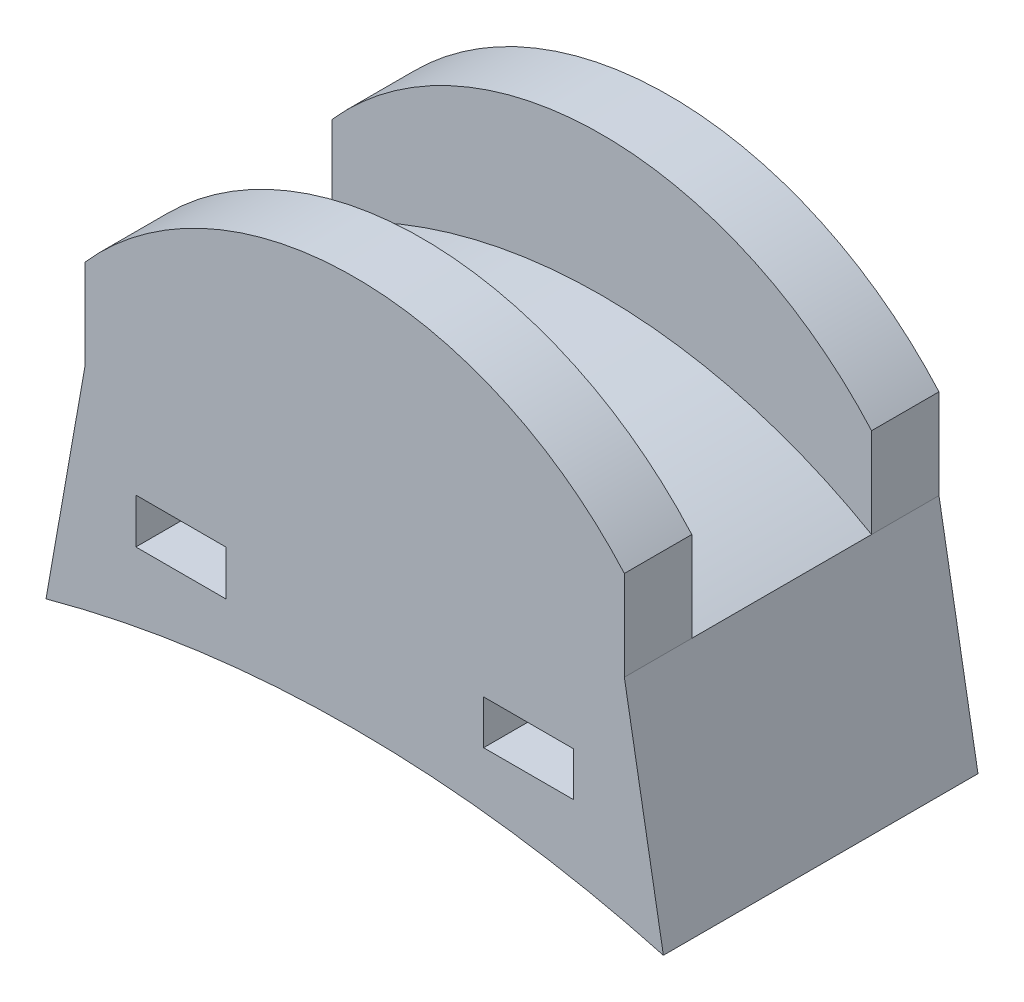
SolidWorks part; units mm, degrees
ref_plane "Front Plane" through (0, 0, 0) normal (0, 0, 1) x (1, 0, 0)
ref_plane "Top Plane" through (0, 0, 0) normal (0, 1, 0) x (1, 0, 0)
ref_plane "Right Plane" through (0, 0, 0) normal (1, 0, 0) x (0, 0, -1)
sketch "Sketch1" plane through (0, 0, 0) normal (0, 0, 1) x (1, 0, 0)
  line L1 (-76.2, 0) -> (-81.7133, -31.2676)
  line L2 (0, 0) -> (5.5133, -31.2676)
  line L3 (-81.7133, -31.2676) -> (5.5133, -31.2676)
  arc A0 (-76.2, 0) -> (0, 0) centre (-38.1, -65.9911) cw
  dimension "D2" = 31.75
  dimension "D1" = 76.2
extrude "Boss-Extrude1" add sketch "Sketch1" along normal blind 25.4
sketch "Sketch2" plane through (0, 0, 25.4) normal (0, 0, 1) x (1, 0, 0)
  line L0 (-38.1, 10.2089) -> (-38.1, 22.9089)
  line L1 (-76.2, 0) -> (-76.2, 12.7)
  line L2 (0, 0) -> (0, 12.7)
  line L3 (0, 0) -> (5.5133, -31.2676)
  line L4 (5.5133, -31.2676) -> (-81.7133, -31.2676)
  line L5 (-81.7133, -31.2676) -> (-76.2, 0)
  arc A0 (0, 0) -> (-76.2, 0) centre (-38.1, -65.9911) ccw construction
  arc A1 (0, 12.7) -> (-76.2, 12.7) centre (-38.1, -20.901) ccw
  dimension "D3" = 12.7
  dimension "D1" = 12.7
  dimension "D2" = 12.7
extrude "Boss-Extrude2" add sketch "Sketch2" along normal blind 9.525
sketch "Sketch3" plane through (0, 0, 0) normal (0, 0, -1) x (-1, 0, 0)
  line L0 (0, 0) -> (0, 12.7)
  line L1 (76.2, 0) -> (76.2, 12.7)
  line L2 (0, 0) -> (-5.5133, -31.2676)
  line L3 (-5.5133, -31.2676) -> (81.7133, -31.2676)
  line L4 (81.7133, -31.2676) -> (76.2, 0)
  arc A0 (0, 12.7) -> (76.2, 12.7) centre (38.1, -20.901) cw
extrude "Boss-Extrude3" add sketch "Sketch3" along normal blind 9.525
sketch "Sketch5" plane through (0, 0, -9.525) normal (0, 0, -1) x (-1, 0, 0)
  line L0 (-5.5133, -31.2676) -> (81.7133, -31.2676)
  arc A0 (-5.5133, -31.2676) -> (81.7133, -31.2676) centre (38.1, -190.503) cw
extrude "Cut-Extrude2" cut sketch "Sketch5" against normal through all
sketch "Sketch6" plane through (0, 0, -9.525) normal (0, 0, -1) x (-1, 0, 0)
  line L1 (7.1867, -12.3446) -> (19.8867, -12.3446)
  line L2 (7.1867, -12.3446) -> (7.1867, -18.5676)
  line L3 (7.1867, -18.5676) -> (19.8867, -18.5676)
  line L4 (19.8867, -12.3446) -> (19.8867, -18.5676)
  line L5 (56.3133, -12.2176) -> (69.0133, -12.2176)
  line L6 (56.3133, -12.2176) -> (56.3133, -18.5676)
  line L7 (56.3133, -18.5676) -> (69.0133, -18.5676)
  line L8 (69.0133, -12.2176) -> (69.0133, -18.5676)
  dimension "D1" = 12.7
  dimension "D2" = 12.7
  dimension "D3" = 6.35
  dimension "D4" = 6.223
  dimension "D5" = 12.7
  dimension "D6" = 12.7
  dimension "D7" = 12.7
  dimension "D8" = 12.7
extrude "Cut-Extrude3" cut sketch "Sketch6" against normal through all
